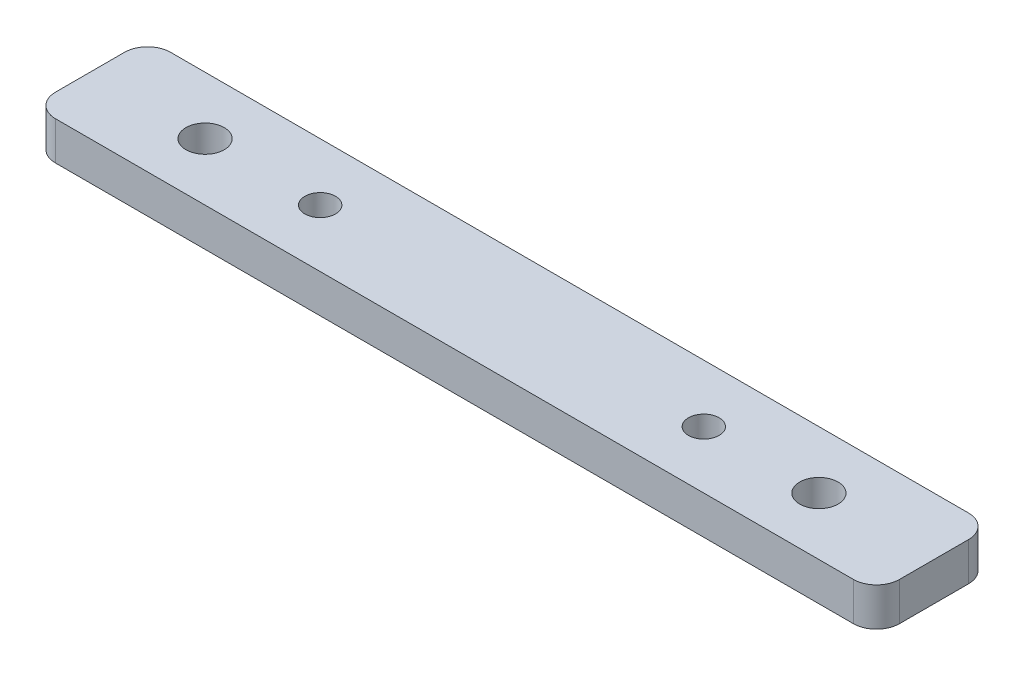
SolidWorks part; units mm, degrees
ref_plane "前视基准面" through (0, 0, 0) normal (0, 0, 1) x (1, 0, 0)
ref_plane "上视基准面" through (0, 0, 0) normal (0, 1, 0) x (1, 0, 0)
ref_plane "右视基准面" through (0, 0, 0) normal (1, 0, 0) x (0, 0, -1)
sketch "草图1" plane through (0, 0, 0) normal (0, 1, 0) x (1, 0, 0)
  line L1 (-55, -7.5) -> (55, -7.5)
  line L2 (-55, -7.5) -> (-55, 7.5)
  line L3 (-55, 7.5) -> (55, 7.5)
  line L4 (55, -7.5) -> (55, 7.5)
  line L5 (-55, -7.5) -> (55, 7.5) construction
  line L6 (-55, 7.5) -> (55, -7.5) construction
  point P0 (0, 0)
  dimension "D1" = 110
  dimension "D2" = 15
extrude "凸台-拉伸1" add sketch "草图1" along normal blind 5
fillet "圆角1" radius 3 4 edges at (-55, 2.5, 7.5) (-55, 2.5, -7.5) (55, 2.5, 7.5) (55, 2.5, -7.5)
sketch "草图2" plane through (0, 5, 0) normal (0, 1, 0) x (1, 0, 0)
  line L0 (0, 7.5) -> (0, 0) construction
  line L1 (52, 7.5) -> (-52, 7.5) construction
  line L2 (0, 0) -> (40, 0) construction
  circle A0 centre (40, 0) radius 2.5
  circle A1 centre (25, 0) radius 2
  circle A2 centre (-40, 0) radius 2.5
  circle A3 centre (-25, 0) radius 2
  dimension "D2" = 5
  dimension "D3" = 25
  dimension "D4" = 4
  dimension "D1" = 40
extrude "切除-拉伸1" cut sketch "草图2" against normal blind 5
